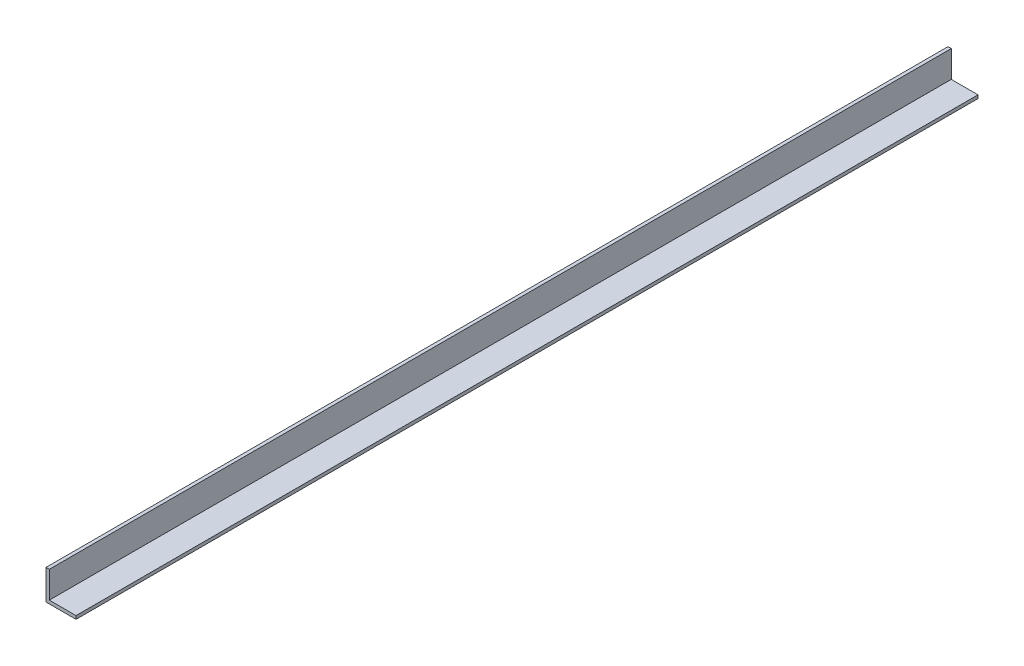
SolidWorks part; units mm, degrees
material "ASTM A36 Acero"
ref_plane "Alzado" through (0, 0, 0) normal (0, 0, 1) x (1, 0, 0)
ref_plane "Planta" through (0, 0, 0) normal (0, 1, 0) x (1, 0, 0)
ref_plane "Vista lateral" through (0, 0, 0) normal (1, 0, 0) x (0, 0, -1)
sketch "Croquis1" plane through (0, 0, 0) normal (0, 0, 1) x (1, 0, 0)
  line L0 (0, 203) -> (0, 0)
  line L1 (0, 0) -> (203, 0)
  line L2 (203, 0) -> (203, 22.23)
  line L3 (203, 22.23) -> (22.23, 22.23)
  line L4 (22.23, 22.23) -> (22.23, 203)
  line L5 (22.23, 203) -> (0, 203)
  dimension "D1" = 22.23
  dimension "D2" = 203
extrude "Saliente-Extruir1" add sketch "Croquis1" against normal blind 6100
